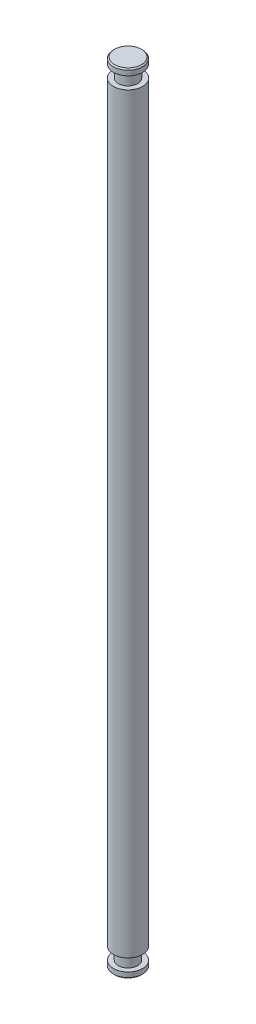
SolidWorks part; units mm, degrees
material "201 Aço inoxidável recozido (SS)"
ref_plane "Frontal" through (0, 0, 0) normal (0, 0, 1) x (1, 0, 0)
ref_plane "Superior" through (0, 0, 0) normal (0, 1, 0) x (1, 0, 0)
ref_plane "Direito" through (0, 0, 0) normal (1, 0, 0) x (0, 0, -1)
sketch "Esboço2" plane through (0, 0, 0) normal (0, 1, 0) x (1, 0, 0)
  circle A0 centre (0, 0) radius 6
  dimension "D1" = 12
extrude "Ressalto-extrusão1" add sketch "Esboço2" along normal blind 324
chamfer "Chanfro1" distance 0.5 angle 45 2 edges at (0, 0, 6) (0, 324, 6)
ref_plane "Plano1" through (0, 5, 0) normal (0, -1, 0) x (-1, 0, 0)
sketch "Esboço3" plane through (0, 5, 0) normal (0, -1, 0) x (-1, 0, 0)
  circle A0 centre (0, 0) radius 4
  circle A1 centre (0, 0) radius 6
  dimension "D1" = 12
  dimension "D2" = 8
extrude "Corte-extrusão1" cut sketch "Esboço3" against normal mid plane 5
ref_plane "Plano2" through (0, 319, 0) normal (0, 1, 0) x (1, 0, 0)
sketch "Esboço4" plane through (0, 319, 0) normal (0, 1, 0) x (1, 0, 0)
  circle A0 centre (0, 0) radius 6
  circle A1 centre (0, 0) radius 4
  dimension "D1" = 8
  dimension "D2" = 12
extrude "Corte-extrusão2" cut sketch "Esboço4" against normal mid plane 5
